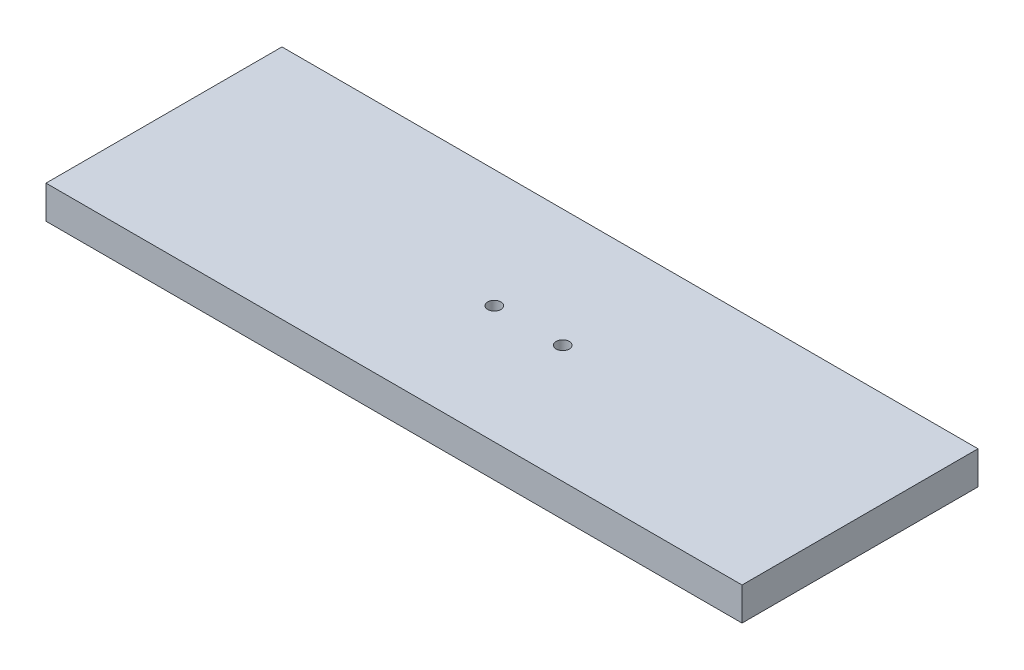
SolidWorks part; units mm, degrees
ref_plane "Front Plane" through (0, 0, 0) normal (0, 0, 1) x (1, 0, 0)
ref_plane "Top Plane" through (0, 0, 0) normal (0, 1, 0) x (1, 0, 0)
ref_plane "Right Plane" through (0, 0, 0) normal (1, 0, 0) x (0, 0, -1)
sketch "Sketch1" plane through (0, 0, 0) normal (0, 0, 1) x (1, 0, 0)
  line L1 (-187.325, 8.89) -> (187.325, 8.89)
  line L2 (-187.325, 8.89) -> (-187.325, -8.89)
  line L3 (-187.325, -8.89) -> (187.325, -8.89)
  line L4 (187.325, 8.89) -> (187.325, -8.89)
  line L5 (-187.325, 8.89) -> (187.325, -8.89) construction
  line L6 (-187.325, -8.89) -> (187.325, 8.89) construction
  point P0 (0, 0)
  dimension "D1" = 374.65
  dimension "D2" = 17.78
extrude "Boss-Extrude1" add sketch "Sketch1" along normal blind 127
sketch "Sketch2" plane through (0, -8.89, 0) normal (0, -1, 0) x (1, 0, 0)
  line L0 (-187.325, 63.5) -> (-9.525, 63.5) construction
  line L1 (-187.325, 127) -> (-187.325, 0) construction
  line L2 (-9.525, 63.5) -> (27.305, 63.5) construction
  circle A0 centre (-9.525, 63.5) radius 3.556
  circle A1 centre (27.305, 63.5) radius 3.556
  dimension "D2" = 7.112
  dimension "D4" = 7.112
  dimension "D1" = 177.8
  dimension "D3" = 36.83
extrude "Cut-Extrude1" cut sketch "Sketch2" against normal through all
